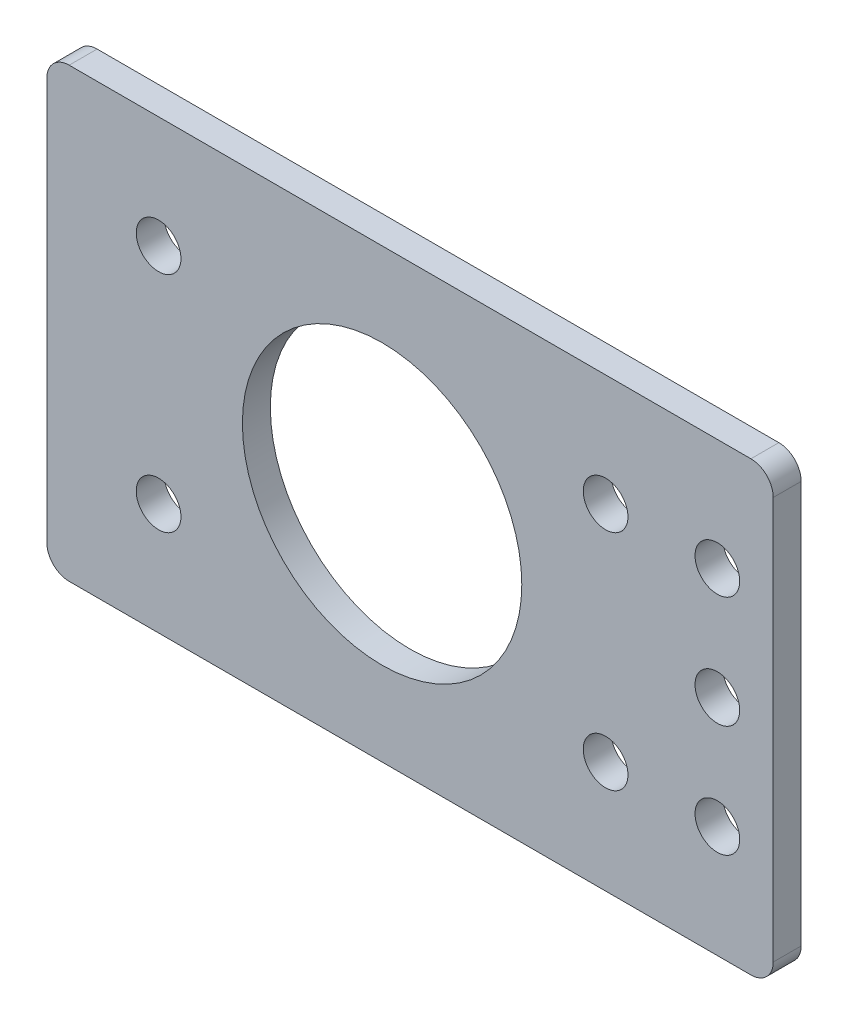
SolidWorks part; units mm, degrees
ref_plane "Front Plane" through (0, 0, 0) normal (0, 0, 1) x (1, 0, 0)
ref_plane "Top Plane" through (0, 0, 0) normal (0, 1, 0) x (1, 0, 0)
ref_plane "Right Plane" through (0, 0, 0) normal (1, 0, 0) x (0, 0, -1)
sketch "Sketch1" plane through (0, 0, 0) normal (0, 0, 1) x (1, 0, 0)
  arc A19 (-480.6, -14.2) -> (-459.2, -14.2) centre (-469.9, 0) ccw
  arc A20 (-446.9968, 12.573) -> (-442.0032, 12.573) centre (-444.5, 12.7) ccw
  arc A21 (-421.5968, 12.573) -> (-416.6032, 12.573) centre (-419.1, 12.7) ccw
  arc A22 (-434.2968, 12.573) -> (-429.3032, 12.573) centre (-431.8, 12.7) ccw
  arc A23 (-434.2968, -0.127) -> (-429.3032, -0.127) centre (-431.8, 0) ccw
  arc A24 (-421.5968, -0.127) -> (-416.6032, -0.127) centre (-419.1, 0) ccw
  arc A25 (-421.5968, -12.827) -> (-416.6032, -12.827) centre (-419.1, -12.7) ccw
  arc A26 (-434.2968, -12.827) -> (-429.3032, -12.827) centre (-431.8, -12.7) ccw
  arc A27 (-446.9968, -12.827) -> (-442.0032, -12.827) centre (-444.5, -12.7) ccw
  arc A28 (-491.5572, 0.127) -> (-494.0059, 2.139) centre (-493.7125, 0) ccw
  arc A29 (-494.0059, -2.139) -> (-491.5572, -0.127) centre (-493.7125, 0) ccw
  arc A30 (-497.7968, 12.573) -> (-492.8032, 12.573) centre (-495.3, 12.7) ccw
  arc A31 (-497.7968, -12.827) -> (-492.8032, -12.827) centre (-495.3, -12.7) ccw
  circle A32 centre (-481.8062, -20.6222) radius 2.159
  circle A33 centre (-457.9938, -20.6222) radius 2.159
  arc A34 (-448.2428, -0.127) -> (-445.7941, -2.139) centre (-446.0875, 0) ccw
  arc A35 (-445.7941, 2.139) -> (-448.2428, 0.127) centre (-446.0875, 0) ccw
  circle A36 centre (-457.9937, 20.6222) radius 2.159
  circle A37 centre (-481.8063, 20.6222) radius 2.159
sketch "Sketch2" plane through (0, 0, 0) normal (0, 0, 1) x (1, 0, 0)
  line L0 (-508, 25.4) -> (-481.6246, 25.4)
  line L1 (-481.6246, 25.4) -> (-457.9938, 25.4)
  line L2 (-457.9938, 25.4) -> (-431.8, 25.4)
  line L3 (-431.8, 25.4) -> (-368.3, 25.4)
  line L4 (-368.3, 25.4) -> (-368.3, -25.4)
  line L5 (-368.3, -25.4) -> (-431.8, -25.4)
  line L6 (-431.8, -25.4) -> (-457.9938, -25.4)
  line L7 (-457.9938, -25.4) -> (-481.6246, -25.4)
  line L8 (-481.6246, -25.4) -> (-508, -25.4)
  line L9 (-508, 25.4) -> (-508, -25.4)
  line L10 (-419.1, 12.7) -> (-406.4, 12.7) construction
  circle A0 centre (-469.9, 0) radius 15.875
  circle A7 centre (-495.3, 12.7) radius 2.54
  circle A8 centre (-495.3, -12.7) radius 2.54
  circle A9 centre (-444.5, -12.7) radius 2.54
  circle A10 centre (-431.8, -12.7) radius 2.54
  circle A11 centre (-419.1, -12.7) radius 2.54
  circle A12 centre (-419.1, 0) radius 2.54
  circle A13 centre (-431.8, 0) radius 2.54
  circle A14 centre (-431.8, 12.7) radius 2.54
  circle A15 centre (-419.1, 12.7) radius 2.54
  circle A16 centre (-444.5, 12.7) radius 2.54
  circle A17 centre (-406.4, 12.7) radius 2.54
  circle A18 centre (-406.4, 0) radius 2.54
  circle A19 centre (-406.4, -12.7) radius 2.54
  circle A20 centre (-393.7, 12.7) radius 2.54
  circle A21 centre (-393.7, 0) radius 2.54
  circle A22 centre (-393.7, -12.7) radius 2.54
  circle A23 centre (-381, 12.7) radius 2.54
  circle A24 centre (-381, 0) radius 2.54
  circle A25 centre (-381, -12.7) radius 2.54
  dimension "D2" = 31.75
  dimension "D3" = 5.08
  dimension "D4" = 50.8
  dimension "D5" = 25.4
  dimension "D8" = 38.1
  dimension "D9" = 38.1
  dimension "D11" = 12.7
  dimension "D12" = 101.6
  dimension "D13" = 50.8
  dimension "D10" = 4
extrude "Boss-Extrude1" add sketch "Sketch2" along normal blind 3.175
fillet "Fillet1" radius 2.54 4 edges at (-368.3, 25.4, 1.5875) (-368.3, -25.4, 1.5875) (-508, -25.4, 1.5875) (-508, 25.4, 1.5875)
sketch "Sketch4" plane through (0, 0, 3.175) normal (0, 0, 1) x (1, 0, 0)
  line L0 (-370.84, 25.4) -> (-505.46, 25.4) construction
  line L1 (-425.45, 25.4) -> (-508, 25.4)
  line L2 (-425.45, 25.4) -> (-425.45, -25.4)
  line L3 (-425.45, -25.4) -> (-508, -25.4)
  line L4 (-508, 25.4) -> (-508, -25.4)
  dimension "D1" = 82.55
extrude "Cut-Extrude1" cut sketch "Sketch4" against normal through all flip side to cut
fillet "Fillet2" radius 2.54 2 edges at (-425.45, -25.4, 1.5875) (-425.45, 25.4, 1.5875)
